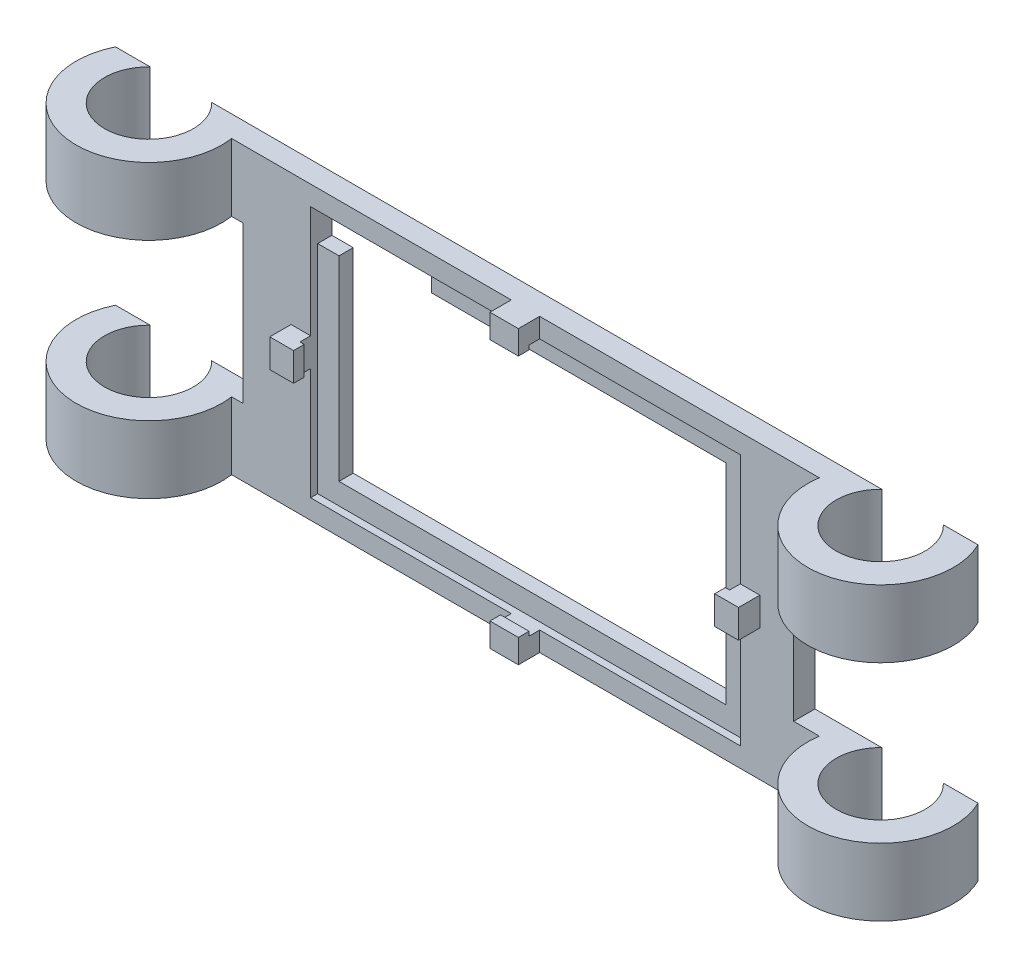
SolidWorks part; units mm, degrees
ref_plane "Front Plane" through (0, 0, 0) normal (0, 0, 1) x (1, 0, 0)
ref_plane "Top Plane" through (0, 0, 0) normal (0, 1, 0) x (1, 0, 0)
ref_plane "Right Plane" through (0, 0, 0) normal (1, 0, 0) x (0, 0, -1)
sketch "Sketch1" plane through (0, 0, 0) normal (0, 1, 0) x (1, 0, 0)
  line L0 (-17.3801, 0) -> (12.2471, 0) construction
  line L1 (0, 14.6335) -> (0, -9.9508) construction
  line L2 (-25.755, 0) -> (-25.755, 5.125) construction
  line L3 (-25.755, 0) -> (-21.1503, 2.25)
  line L4 (-25.755, 0) -> (-30.3597, 2.25)
  line L5 (25.755, 0) -> (30.3597, 2.25)
  line L6 (25.755, 0) -> (21.1503, 2.25)
  line L7 (-21.1503, 2.25) -> (21.1503, 2.25)
  line L8 (-20.6852, 0.75) -> (20.6852, 0.75)
  line L9 (-30.3597, 2.25) -> (-21.1503, 2.25)
  line L10 (21.1503, 2.25) -> (30.3597, 2.25)
  circle A0 centre (-25.755, 0) radius 3.125
  circle A1 centre (25.755, 0) radius 3.125
  circle A2 centre (-25.755, 0) radius 5.125
  circle A3 centre (25.755, 0) radius 5.125
  dimension "D2" = 6.25
  dimension "D3" = 2
  dimension "D1" = 51.51
  dimension "D4" = 1.5
  dimension "D5" = 1.5
extrude "Boss-Extrude1" add sketch "Sketch1" along normal blind 20.5 contours A2 L3 A0 L4 | L8 A3 L7 A2 | A3 L5 A1 L6 | L6 A1 L10 | L10 A1 L5 | A0 L3 L9 | A0 L9 L4
sketch "Sketch2" plane through (0, 0, -2.25) normal (0, 0, -1) x (-1, 0, 0)
  line L0 (-30.88, 20.5) -> (-30.88, 0) construction
  line L1 (-30.88, 15.75) -> (-19.88, 15.75)
  line L2 (-30.88, 15.75) -> (-30.88, 4.75)
  line L3 (-30.88, 4.75) -> (-19.88, 4.75)
  line L4 (-19.88, 15.75) -> (-19.88, 4.75)
  line L5 (30.88, 10.25) -> (-30.88, 10.25) construction
  line L7 (30.88, 0) -> (30.88, 20.5) construction
  line L8 (-19.88, 10.25) -> (-30.88, 10.25) construction
  line L9 (0, 0) -> (0, 20.5) construction
  line L10 (23.5863, 20.5) -> (-23.5863, 20.5) construction
  line L11 (19.88, 15.75) -> (19.88, 4.75)
  line L12 (30.88, 4.75) -> (19.88, 4.75)
  line L13 (30.88, 15.75) -> (30.88, 4.75)
  line L14 (30.88, 15.75) -> (19.88, 15.75)
  dimension "D1" = 11
  dimension "D2" = 11
extrude "Cut-Extrude1" cut sketch "Sketch2" against normal through all
sketch "Sketch3" plane through (0, 0, -0.75) normal (0, 0, 1) x (1, 0, 0)
  line L0 (0, 20.5) -> (0, 0) construction
  line L1 (-20.6852, 20.5) -> (20.6852, 20.5) construction
  line L2 (-19.88, 10.25) -> (19.88, 10.25) construction
  line L3 (-19.88, 15.75) -> (-19.88, 4.75) construction
  line L4 (19.88, 4.75) -> (19.88, 15.75) construction
  line L6 (-15.125, 19.125) -> (15.125, 19.125)
  line L7 (-15.125, 19.125) -> (-15.125, 1.375)
  line L8 (-15.125, 1.375) -> (15.125, 1.375)
  line L9 (15.125, 19.125) -> (15.125, 1.375)
  line L10 (-15.125, 19.125) -> (15.125, 1.375) construction
  line L11 (-15.125, 1.375) -> (15.125, 19.125) construction
  point P11 (0, 10.25)
  dimension "D1" = 30.25
  dimension "D2" = 17.75
extrude "Cut-Extrude2" cut sketch "Sketch3" against normal blind 0.5
sketch "Sketch4" plane through (0, 0, -1.25) normal (0, 0, 1) x (1, 0, 0)
  line L4 (15.125, 1.375) -> (15.125, 19.125)
  line L5 (15.125, 19.125) -> (-15.125, 19.125)
  line L6 (-15.125, 19.125) -> (-15.125, 1.375)
  line L7 (-15.125, 1.375) -> (15.125, 1.375)
  line L8 (15.125, 1.375) -> (15.125, 19.125)
  line L9 (15.125, 19.125) -> (-15.125, 19.125)
  line L10 (-15.125, 19.125) -> (-15.125, 1.375)
  line L11 (-15.125, 1.375) -> (15.125, 1.375)
  line L16 (13.625, 2.875) -> (13.625, 17.625)
  line L17 (13.625, 17.625) -> (-13.625, 17.625)
  line L18 (-13.625, 17.625) -> (-13.625, 2.875)
  line L19 (-13.625, 2.875) -> (13.625, 2.875)
  line L20 (13.625, 2.875) -> (13.625, 17.625)
  line L21 (13.625, 17.625) -> (-13.625, 17.625)
  line L22 (-13.625, 17.625) -> (-13.625, 2.875)
  line L23 (-13.625, 2.875) -> (13.625, 2.875)
  dimension "D1" = 0
  dimension "D2" = 1.5
extrude "Cut-Extrude3" cut sketch "Sketch4" against normal up to next contours L22 L23 L20 L21
sketch "Sketch5" plane through (0, 0, -0.75) normal (0, 0, 1) x (1, 0, 0)
  line L0 (0, 20.5) -> (0, 0) construction
  line L1 (-20.6852, 20.5) -> (20.6852, 20.5) construction
  line L2 (-19.88, 10.25) -> (19.88, 10.25) construction
  line L3 (-19.88, 15.75) -> (-19.88, 4.75) construction
  line L4 (19.88, 4.75) -> (19.88, 15.75) construction
  line L5 (1, 20.5) -> (1, 19.125)
  line L6 (1, 20.5) -> (-1, 20.5)
  line L7 (1, 19.125) -> (-1, 19.125)
  line L8 (-1, 20.5) -> (-1, 19.125)
  line L9 (1, 20.5) -> (-1, 19.125) construction
  line L10 (1, 19.125) -> (-1, 20.5) construction
  line L11 (15.125, 19.125) -> (-15.125, 19.125) construction
  line L12 (1, 0) -> (1, 1.375)
  line L13 (1, 1.375) -> (-1, 1.375)
  line L14 (-1, 0) -> (-1, 1.375)
  line L15 (1, 0) -> (-1, 0)
  line L16 (-16.5, 11.25) -> (-15.125, 11.25)
  line L17 (-16.5, 11.25) -> (-16.5, 9.25)
  line L18 (-15.125, 11.25) -> (-15.125, 9.25)
  line L19 (-16.5, 9.25) -> (-15.125, 9.25)
  line L20 (-16.5, 11.25) -> (-15.125, 9.25) construction
  line L21 (-15.125, 11.25) -> (-16.5, 9.25) construction
  line L22 (-15.125, 19.125) -> (-15.125, 1.375) construction
  line L23 (16.5, 9.25) -> (15.125, 9.25)
  line L24 (15.125, 11.25) -> (15.125, 9.25)
  line L25 (16.5, 11.25) -> (15.125, 11.25)
  line L26 (16.5, 11.25) -> (16.5, 9.25)
  point P12 (0, 19.8125)
  point P23 (-15.8125, 10.25)
  dimension "D1" = 2
extrude "Boss-Extrude2" add sketch "Sketch5" along normal blind 0.75
sketch "Sketch6" plane through (0, 0, 0) normal (0, 0, 1) x (1, 0, 0)
  line L0 (-16.5, 11.25) -> (-16.5, 9.25) construction
  line L1 (-16.5, 9.25) -> (-15.125, 9.25) construction
  line L2 (-15.125, 9.25) -> (-15.125, 11.25) construction
  line L3 (-15.125, 11.25) -> (-16.5, 11.25) construction
  line L4 (-1, 0) -> (1, 0) construction
  line L5 (1, 0) -> (1, 1.375) construction
  line L6 (1, 1.375) -> (-1, 1.375) construction
  line L7 (-1, 1.375) -> (-1, 0) construction
  line L8 (1, 20.5) -> (-1, 20.5) construction
  line L9 (-1, 20.5) -> (-1, 19.125) construction
  line L10 (-1, 19.125) -> (1, 19.125) construction
  line L11 (1, 19.125) -> (1, 20.5) construction
  line L12 (16.5, 9.25) -> (16.5, 11.25) construction
  line L13 (16.5, 11.25) -> (15.125, 11.25) construction
  line L14 (15.125, 11.25) -> (15.125, 9.25) construction
  line L15 (15.125, 9.25) -> (16.5, 9.25) construction
  line L16 (-16.5, 11.25) -> (-16.5, 9.25)
  line L17 (-16.5, 9.25) -> (-15.125, 9.25)
  line L18 (-15.125, 9.25) -> (-15.125, 11.25)
  line L19 (-15.125, 11.25) -> (-16.5, 11.25)
  line L20 (-1, 0) -> (1, 0)
  line L21 (1, 0) -> (1, 1.375)
  line L22 (1, 1.375) -> (-1, 1.375)
  line L23 (-1, 1.375) -> (-1, 0)
  line L24 (1, 20.5) -> (-1, 20.5)
  line L25 (-1, 20.5) -> (-1, 19.125)
  line L26 (-1, 19.125) -> (1, 19.125)
  line L27 (1, 19.125) -> (1, 20.5)
  line L28 (16.5, 9.25) -> (16.5, 11.25)
  line L29 (16.5, 11.25) -> (15.125, 11.25)
  line L30 (15.125, 11.25) -> (15.125, 9.25)
  line L31 (15.125, 9.25) -> (16.5, 9.25)
  line L33 (-15.125, 11.25) -> (-14.825, 11.25)
  line L34 (-15.125, 11.25) -> (-15.125, 9.25)
  line L35 (-15.125, 9.25) -> (-14.825, 9.25)
  line L36 (-14.825, 11.25) -> (-14.825, 9.25)
  line L37 (-1, 19.125) -> (1, 19.125)
  line L38 (-1, 19.125) -> (-1, 18.825)
  line L39 (-1, 18.825) -> (1, 18.825)
  line L40 (1, 19.125) -> (1, 18.825)
  line L41 (15.125, 11.25) -> (14.825, 11.25)
  line L42 (15.125, 11.25) -> (15.125, 9.25)
  line L43 (15.125, 9.25) -> (14.825, 9.25)
  line L44 (14.825, 11.25) -> (14.825, 9.25)
  line L45 (-1, 1.375) -> (1, 1.375)
  line L46 (-1, 1.375) -> (-1, 1.675)
  line L47 (-1, 1.675) -> (1, 1.675)
  line L48 (1, 1.375) -> (1, 1.675)
  line M1 (-16.5, 11.25) -> (-16.5, 9.25)
  line M2 (-16.5, 9.25) -> (-15.125, 9.25)
  line M3 (-15.125, 9.25) -> (-15.125, 11.25)
  line M4 (-15.125, 11.25) -> (-16.5, 11.25)
  dimension "D1" = 0.3
extrude "Boss-Extrude3" add sketch "Sketch6" along normal blind 0.75 contours M4 M1 M2 M3 | L36 L33 L35 M3 | L22 L48 L47 L46 | L22 L23 L20 L21 | L41 L44 L43 L30 | L30 L31 L28 L29 | L26 L27 L24 L25 | L40 L26 L38 L39
sketch "Sketch7" plane through (0, 0, -1.25) normal (0, 0, 1) x (1, 0, 0)
  line L1 (-15.125, 19.125) -> (-7.125, 19.125)
  line L2 (-15.125, 19.125) -> (-15.125, 16.625)
  line L3 (-15.125, 16.625) -> (-7.125, 16.625)
  line L4 (-7.125, 19.125) -> (-7.125, 16.625)
  dimension "D1" = 8
  dimension "D2" = 2.5
extrude "Cut-Extrude4" cut sketch "Sketch7" against normal through all
sketch "Sketch8" plane through (0, 0, -0.75) normal (0, 0, 1) x (1, 0, 0)
  line L0 (20.6852, 4.75) -> (19.88, 4.75) construction
  line L1 (19.88, 15.75) -> (18.88, 15.75)
  line L2 (19.88, 15.75) -> (19.88, 4.75)
  line L3 (19.88, 4.75) -> (18.88, 4.75)
  line L4 (18.88, 15.75) -> (18.88, 4.75)
  dimension "D1" = 1
extrude "Cut-Extrude5" cut sketch "Sketch8" against normal up to next
